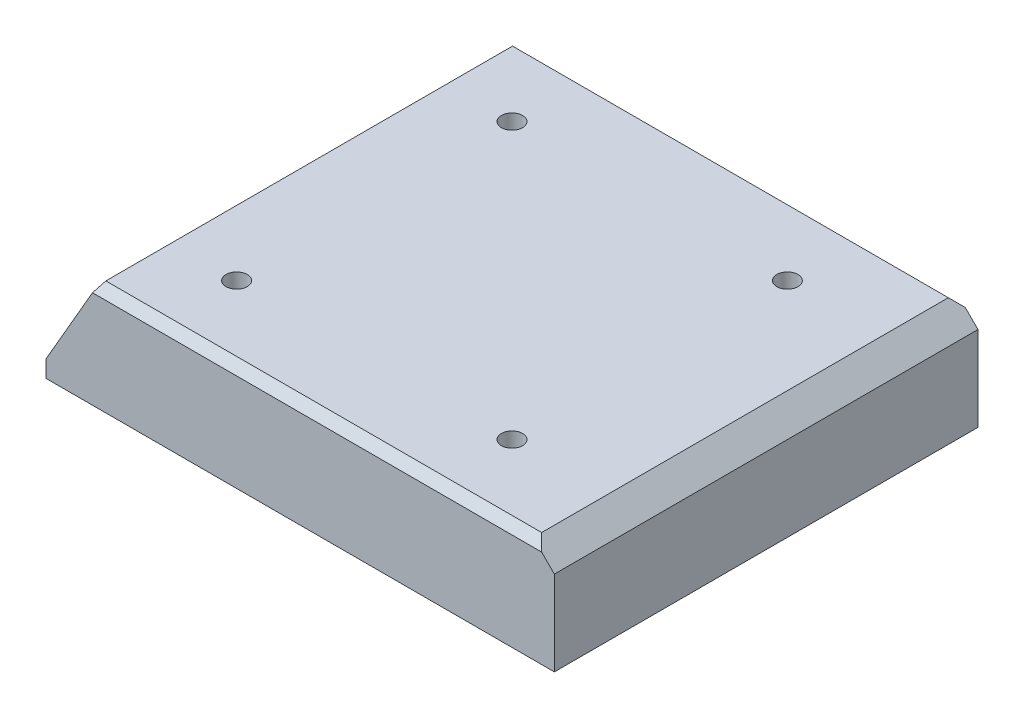
SolidWorks part; units mm, degrees
ref_plane "Front Plane" through (0, 0, 0) normal (0, 0, 1) x (1, 0, 0)
ref_plane "Top Plane" through (0, 0, 0) normal (0, 1, 0) x (1, 0, 0)
ref_plane "Right Plane" through (0, 0, 0) normal (1, 0, 0) x (0, 0, -1)
sketch "Sketch1" plane through (0, 0, 0) normal (0, 0, 1) x (1, 0, 0)
  line L0 (-60, 0) -> (60, 0)
  line L1 (60, 0) -> (60, 20)
  line L2 (60, 20) -> (55, 25)
  line L3 (55, 25) -> (-47.8756, 25)
  line L4 (-47.8756, 25) -> (-60, 4)
  line L5 (-60, 4) -> (-60, 0)
  point P4 (0, 0)
  dimension "D1" = 120
  dimension "D2" = 4
  dimension "D3" = 25
  dimension "D4" = 5
  dimension "D5" = 45
  dimension "D6" = 30
extrude "Boss-Extrude1" add sketch "Sketch1" along normal mid plane 100
sketch "Sketch2" plane through (0, 25, 0) normal (0, 1, 0) x (1, 0, 0)
  line L0 (60, -50) -> (60, 50) construction
  line L1 (55, 50) -> (-47.8756, 50) construction
  line L2 (0, 0) -> (-32.5, 0)
  circle A0 centre (-32.5, 32.5) radius 2.5
  circle A1 centre (32.5, 32.5) radius 2.5
  circle A2 centre (32.5, -32.5) radius 2.5
  circle A3 centre (-32.5, -32.5) radius 2.5
  dimension "D1" = 27.5
  dimension "D4" = 17.5
  dimension "D5" = 5
  dimension "D2" = 65
  dimension "D3" = 17.5
extrude "Cut-Extrude1" cut sketch "Sketch2" against normal through all contours A3 | A0
mirror "Mirror1" about plane through (0, 0, 0) normal (1, 0, 0) of "Cut-Extrude1"
sketch "Sketch3" plane through (-46.7321, 26.9808, 0) normal (-0.866, 0.5, 0) x (0, 0, 1)
  line L0 (50, -26.5359) -> (-50, -26.5359) construction
  circle A0 centre (-25, -14.4115) radius 1.5
  circle A2 centre (27, -14.4115) radius 1.5
  dimension "D1" = 52
  dimension "D2" = 25
  dimension "D3" = 3
  dimension "D4" = 12.1244
extrude "Cut-Extrude2" cut sketch "Sketch3" against normal blind 12.4
chamfer "Chamfer1" distance 2 angle 45 2 edges at (3.5622, 25, -50) (3.5622, 25, 50)
